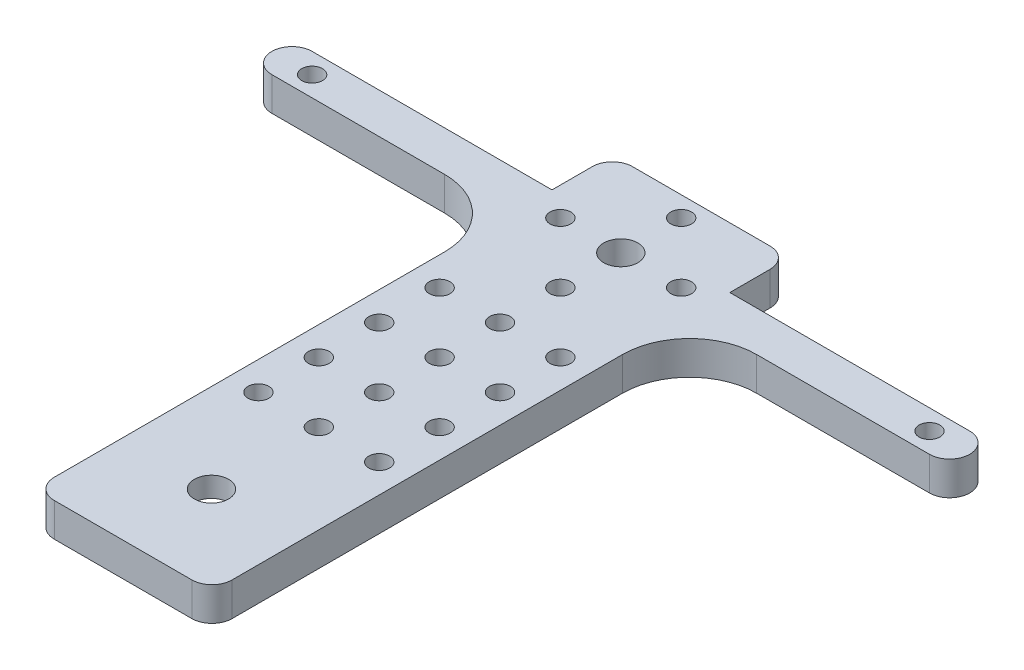
SolidWorks part; units mm, degrees
ref_plane "Front Plane" through (0, 0, 0) normal (0, 0, 1) x (1, 0, 0)
ref_plane "Top Plane" through (0, 0, 0) normal (0, 1, 0) x (1, 0, 0)
ref_plane "Right Plane" through (0, 0, 0) normal (1, 0, 0) x (0, 0, -1)
sketch "Sketch1" plane through (0, 0, 0) normal (0, 1, 0) x (1, 0, 0)
  line L0 (0, 0) -> (-46, 0) construction
  line L1 (-49, 3) -> (-13.25, 3)
  line L3 (-10.25, 12) -> (10.25, 12)
  line L5 (0, 0) -> (0, 20.2225) construction
  line L9 (-49, -3) -> (-23.25, -3)
  line L10 (-13.25, 3) -> (-13.25, 9)
  line L11 (13.25, 3) -> (13.25, 9)
  line L12 (0, 0) -> (0, 9)
  line L13 (0, 0) -> (0, -61)
  line L14 (-13.25, -47.8265) -> (13.25, -47.8265) construction
  line L16 (10.25, -74.1735) -> (-10.25, -74.1735)
  line L17 (-13.25, -71.1735) -> (-13.25, -47.8265)
  line L18 (49, 3) -> (13.25, 3)
  line L19 (-13.25, -47.8265) -> (-13.25, -13)
  line L20 (13.25, -47.8265) -> (13.25, -13)
  line L25 (49, -3) -> (23.25, -3)
  line L26 (0, -18) -> (0, -9)
  line L27 (13.25, -71.1735) -> (13.25, -47.8265)
  line L28 (-11.5, -49.5) -> (11.5, -72.5) construction
  line L33 (-9.5, -72.5) -> (9.5, -72.5)
  line L34 (-11.5, -70.5) -> (-11.5, -51.5)
  line L35 (-9.5, -49.5) -> (9.5, -49.5)
  line L36 (11.5, -70.5) -> (11.5, -51.5)
  circle A0 centre (-46, 0) radius 1.55
  circle A2 centre (46, 0) radius 1.55
  arc A4 (-10.25, 12) -> (-13.25, 9) centre (-10.25, 9) ccw
  arc A7 (13.25, 9) -> (10.25, 12) centre (10.25, 9) ccw
  circle A8 centre (0, 0) radius 2.55
  circle A9 centre (0, 9) radius 1.55
  circle A10 centre (9, 0) radius 1.55
  circle A11 centre (0, -9) radius 1.55
  circle A12 centre (-9, 0) radius 1.55
  arc A13 (10.25, -74.1735) -> (13.25, -71.1735) centre (10.25, -71.1735) ccw
  arc A14 (-10.25, -74.1735) -> (-13.25, -71.1735) centre (-10.25, -71.1735) cw
  arc A15 (23.25, -3) -> (13.25, -13) centre (23.25, -13) ccw
  arc A16 (-13.25, -13) -> (-23.25, -3) centre (-23.25, -13) ccw
  arc A17 (-49, 3) -> (-49, -3) centre (-49, 0) ccw
  arc A18 (49, 3) -> (49, -3) centre (49, 0) cw
  circle A19 centre (46, 0) radius 1.55
  circle A20 centre (-9, -18) radius 1.55
  circle A21 centre (9, -18) radius 1.55
  circle A22 centre (-9, -27) radius 1.55
  circle A23 centre (9, -27) radius 1.55
  circle A24 centre (-9, -36) radius 1.55
  circle A25 centre (9, -36) radius 1.55
  circle A26 centre (-9, -45) radius 1.55
  circle A27 centre (9, -45) radius 1.55
  circle A28 centre (0, -18) radius 1.55
  circle A29 centre (0, -27) radius 1.55
  circle A30 centre (0, -36) radius 1.55
  circle A31 centre (0, -45) radius 1.55
  arc A33 (9.5, -49.5) -> (11.5, -51.5) centre (9.5, -51.5) cw
  arc A34 (11.5, -70.5) -> (9.5, -72.5) centre (9.5, -70.5) cw
  arc A35 (-9.5, -72.5) -> (-11.5, -70.5) centre (-9.5, -70.5) cw
  arc A36 (-11.5, -51.5) -> (-9.5, -49.5) centre (-9.5, -51.5) cw
  circle A37 centre (0, -61) radius 2.55
  point P16 (0, 12)
  point P22 (12, 0)
  point P23 (-12, 0)
  point P25 (0, -12)
  point P28 (-13.25, 12)
  point P31 (-13.25, -12)
  point P34 (13.25, -12)
  point P37 (13.25, 12)
  point P47 (0, 0)
  point P54 (0, -61)
  point P58 (13.25, -3)
  point P95 (-11.5, -72.5)
  dimension "D1" = 3
  dimension "D2" = 4
  dimension "D3" = 3
  dimension "D9" = 10
  dimension "D10" = 4
  dimension "D13" = 2
  dimension "D14" = 5.1
  dimension "D16" = 5.1
  dimension "D4" = 23
  dimension "D5" = 23
  dimension "D6" = 2
  dimension "D7" = 13.25
  dimension "D8" = 13.25
  dimension "D15" = 61
  dimension "D11" = 2
  dimension "D12" = 4
extrude "Boss-Extrude1" add sketch "Sketch1" along normal blind 5
sketch "Sketch2" plane through (0, 0, 0) normal (0, -1, 0) x (1, 0, 0)
  line L3 (0, 0) -> (0, -9) construction
  line L4 (0, 0) -> (0, 61) construction
  line L5 (0, 18) -> (0, 9) construction
  line L6 (0, 0) -> (0, -9)
  line L7 (-11.5, 70.5) -> (-11.5, 51.5)
  line L12 (9.5, 72.5) -> (-9.5, 72.5)
  line L13 (11.5, 51.5) -> (11.5, 70.5)
  line L14 (-9.5, 49.5) -> (9.5, 49.5)
  line L15 (-11.5, 70.5) -> (-11.5, 51.5)
  line L16 (9.5, 72.5) -> (-9.5, 72.5)
  line L17 (11.5, 51.5) -> (11.5, 70.5)
  line L18 (-9.5, 49.5) -> (9.5, 49.5)
  line L19 (-23.25, 3) -> (-49, 3)
  line L20 (-49, -3) -> (-13.25, -3)
  line L21 (-13.25, -3) -> (-13.25, -9)
  line L22 (-10.25, -12) -> (10.25, -12)
  line L23 (13.25, -9) -> (13.25, -3)
  line L24 (13.25, -3) -> (49, -3)
  line L25 (49, 3) -> (23.25, 3)
  line L26 (13.25, 13) -> (13.25, 47.8265)
  line L27 (13.25, 47.8265) -> (13.25, 71.1735)
  line L28 (10.25, 74.1735) -> (-10.25, 74.1735)
  line L29 (-13.25, 71.1735) -> (-13.25, 47.8265)
  line L30 (-13.25, 47.8265) -> (-13.25, 13)
  line L31 (-23.25, 3) -> (-49, 3)
  line L44 (-49, -3) -> (-13.25, -3)
  line L45 (-13.25, -3) -> (-13.25, -9)
  line L46 (-10.25, -12) -> (10.25, -12)
  line L47 (13.25, -9) -> (13.25, -3)
  line L48 (13.25, -3) -> (49, -3)
  line L49 (49, 3) -> (23.25, 3)
  line L51 (13.25, 13) -> (13.25, 47.8265)
  line L52 (13.25, 47.8265) -> (13.25, 71.1735)
  line L53 (10.25, 74.1735) -> (-10.25, 74.1735)
  line L54 (-13.25, 71.1735) -> (-13.25, 47.8265)
  line L55 (-13.25, 47.8265) -> (-13.25, 13)
  line L56 (0, 0) -> (0, 61)
  line L57 (0, 18) -> (0, 9)
  circle A1 centre (0, 0) radius 2.55
  circle A3 centre (0, 0) radius 2.55
  circle A5 centre (46, 0) radius 1.55
  circle A7 centre (46, 0) radius 1.55
  circle A9 centre (-46, 0) radius 1.55
  circle A11 centre (-46, 0) radius 1.55
  circle A13 centre (-9, 0) radius 1.55
  circle A15 centre (-9, 0) radius 1.55
  circle A17 centre (0, 9) radius 1.55
  circle A19 centre (0, 9) radius 1.55
  circle A21 centre (9, 0) radius 1.55
  circle A23 centre (9, 0) radius 1.55
  circle A24 centre (0, -9) radius 1.55
  circle A25 centre (0, -9) radius 1.55
  circle A26 centre (46, 0) radius 1.55
  circle A27 centre (46, 0) radius 1.55
  circle A28 centre (9, 36) radius 1.55
  circle A29 centre (9, 36) radius 1.55
  circle A30 centre (-9, 36) radius 1.55
  circle A31 centre (-9, 36) radius 1.55
  circle A41 centre (9, 27) radius 1.55
  circle A43 centre (9, 27) radius 1.55
  circle A45 centre (-9, 27) radius 1.55
  arc A47 (-49, 3) -> (-49, -3) centre (-49, 0) ccw
  arc A49 (-13.25, -9) -> (-10.25, -12) centre (-10.25, -9) ccw
  arc A51 (10.25, -12) -> (13.25, -9) centre (10.25, -9) ccw
  arc A53 (49, -3) -> (49, 3) centre (49, 0) ccw
  arc A55 (13.25, 13) -> (23.25, 3) centre (23.25, 13) ccw
  arc A57 (13.25, 71.1735) -> (10.25, 74.1735) centre (10.25, 71.1735) ccw
  arc A58 (-10.25, 74.1735) -> (-13.25, 71.1735) centre (-10.25, 71.1735) ccw
  arc A59 (-23.25, 3) -> (-13.25, 13) centre (-23.25, 13) ccw
  arc A60 (-49, 3) -> (-49, -3) centre (-49, 0) ccw
  arc A61 (-13.25, -9) -> (-10.25, -12) centre (-10.25, -9) ccw
  arc A62 (10.25, -12) -> (13.25, -9) centre (10.25, -9) ccw
  arc A63 (49, -3) -> (49, 3) centre (49, 0) ccw
  arc A64 (13.25, 13) -> (23.25, 3) centre (23.25, 13) ccw
  arc A65 (13.25, 71.1735) -> (10.25, 74.1735) centre (10.25, 71.1735) ccw
  arc A66 (-10.25, 74.1735) -> (-13.25, 71.1735) centre (-10.25, 71.1735) ccw
  arc A67 (-23.25, 3) -> (-13.25, 13) centre (-23.25, 13) ccw
  circle A68 centre (-9, 27) radius 1.55
  circle A69 centre (9, 18) radius 1.55
  circle A70 centre (9, 18) radius 1.55
  circle A71 centre (-9, 18) radius 1.55
  circle A72 centre (-9, 18) radius 1.55
  circle A73 centre (0, 45) radius 1.55
  circle A74 centre (0, 45) radius 1.55
  circle A75 centre (0, 36) radius 1.55
  circle A76 centre (0, 36) radius 1.55
  circle A77 centre (0, 27) radius 1.55
  circle A78 centre (0, 27) radius 1.55
  circle A79 centre (0, 18) radius 1.55
  circle A80 centre (0, 18) radius 1.55
  circle A81 centre (9, 45) radius 1.55
  circle A82 centre (9, 45) radius 1.55
  circle A83 centre (-9, 45) radius 1.55
  circle A84 centre (-9, 45) radius 1.55
  arc A88 (-9.5, 72.5) -> (-11.5, 70.5) centre (-9.5, 70.5) ccw
  arc A89 (11.5, 70.5) -> (9.5, 72.5) centre (9.5, 70.5) ccw
  arc A90 (9.5, 49.5) -> (11.5, 51.5) centre (9.5, 51.5) ccw
  arc A91 (-11.5, 51.5) -> (-9.5, 49.5) centre (-9.5, 51.5) ccw
  arc A92 (-9.5, 72.5) -> (-11.5, 70.5) centre (-9.5, 70.5) ccw
  arc A93 (11.5, 70.5) -> (9.5, 72.5) centre (9.5, 70.5) ccw
  arc A94 (9.5, 49.5) -> (11.5, 51.5) centre (9.5, 51.5) ccw
  arc A95 (-11.5, 51.5) -> (-9.5, 49.5) centre (-9.5, 51.5) ccw
  dimension "D1" = 0
  dimension "D2" = 0
  dimension "D3" = 0
  dimension "D4" = 0
  dimension "D5" = 0
  dimension "D6" = 0
  dimension "D7" = 0
  dimension "D8" = 0
  dimension "D9" = 0
  dimension "D10" = 0
  dimension "D11" = 0
  dimension "D12" = 0
  dimension "D13" = 0
  dimension "D14" = 0
  dimension "D15" = 0
  dimension "D16" = 0
  dimension "D17" = 0
  dimension "D18" = 0
  dimension "D19" = 0
  dimension "D20" = 0
  dimension "D21" = 0
  dimension "D22" = 0
extrude "Cut-Extrude1" cut sketch "Sketch2" against normal blind 2
